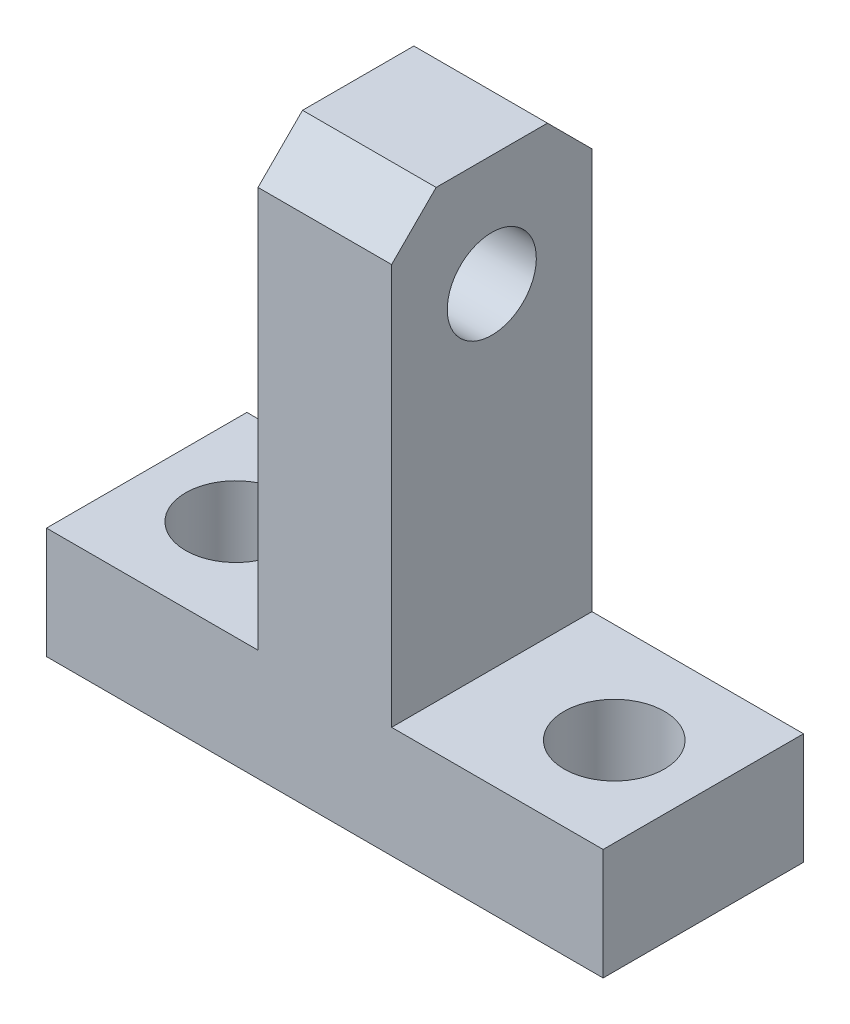
SolidWorks part; units mm, degrees
ref_plane "Front Plane" through (0, 0, 0) normal (0, 0, 1) x (1, 0, 0)
ref_plane "Top Plane" through (0, 0, 0) normal (0, 1, 0) x (1, 0, 0)
ref_plane "Right Plane" through (0, 0, 0) normal (1, 0, 0) x (0, 0, -1)
sketch "Sketch1" plane through (0, 0, 0) normal (0, 0, 1) x (1, 0, 0)
  line L0 (12.5, 0) -> (-12.5, 0)
  line L1 (-12.5, 0) -> (-12.5, 5)
  line L2 (-12.5, 5) -> (-3, 5)
  line L7 (-3, 5) -> (-3, 25)
  line L8 (-3, 25) -> (3, 25)
  line L9 (3, 25) -> (3, 5)
  line L10 (3, 5) -> (12.5, 5)
  line L11 (12.5, 5) -> (12.5, 0)
  line L12 (0, 0) -> (0, 25) construction
  dimension "S" = 5
  dimension "B" = 25
  dimension "A" = 25
  dimension "W" = 6
extrude "Boss-Extrude1" add sketch "Sketch1" along normal mid plane 9
ref_plane "Plane1" through (0, 5, 0) normal (0, 1, 0) x (1, 0, 0)
hole_wizard "Diameter Hole1" positions "Sketch3" profile "Sketch2" hole size "Ø4.5" standard "JIS" end condition through all
sketch "Sketch3" plane through (0, 5, 0) normal (0, 1, 0) x (1, 0, 0)
  line L0 (-8.5, 0) -> (8.5, 0) construction
  line L4 (0, 4.5) -> (0, -4.5) construction
  line L6 (3, 4.5) -> (-3, 4.5) construction
  point P0 (-8.5, 0)
  point P2 (8.5, 0)
  dimension "F" = 17
sketch "Sketch2" plane through (-8.5, 5, 0) normal (1, 0, 0) x (0, 0, 1)
  line L0 (0, 0) -> (0, 5)
  line L1 (0, 5) -> (2.25, 5)
  line L2 (2.25, 5) -> (2.25, 0)
  line L5 (2.25, 0) -> (0, 0)
  line L11 (0, 0) -> (0, 5) construction
  dimension "D_s_1" = 4.5
  dimension "Thru Hole Depth" = 5
chamfer "Chamfer1" distance 2 angle 45 2 edges at (0, 25, -4.5) (0, 25, 4.5)
sketch "Sketch4" plane through (3, 0, 0) normal (1, 0, 0) x (0, 0, -1)
  line L0 (0, 0) -> (0, 25) construction
  line L2 (-2.5, 25) -> (2.5, 25) construction
  circle A0 centre (0, 20) radius 2
  dimension "H" = 20
  dimension "D" = 4
extrude "Cut-Extrude1" cut sketch "Sketch4" against normal through all
sketch "Sketch5" [suppressed] plane through (4, 0, 0) normal (1, 0, 0) x (0, 0, -1)
  line L0 (0, 20) -> (0, 0) construction
  line L1 (-2.5, 20) -> (2.5, 20) construction
  line L2 (-4.5, 0) -> (4.5, 0) construction
  circle A0 centre (0, 15) radius 3
  circle A1 centre (0, 15) radius 2 construction
  dimension "D1" = 6
  dimension "H" = 20
  dimension "D" = 4
extrude "Cut-Extrude2" [suppressed] cut sketch "Sketch5" against normal through all
equation "\"D1@Sketch5\"=\"D@Sketch5\"+2"
